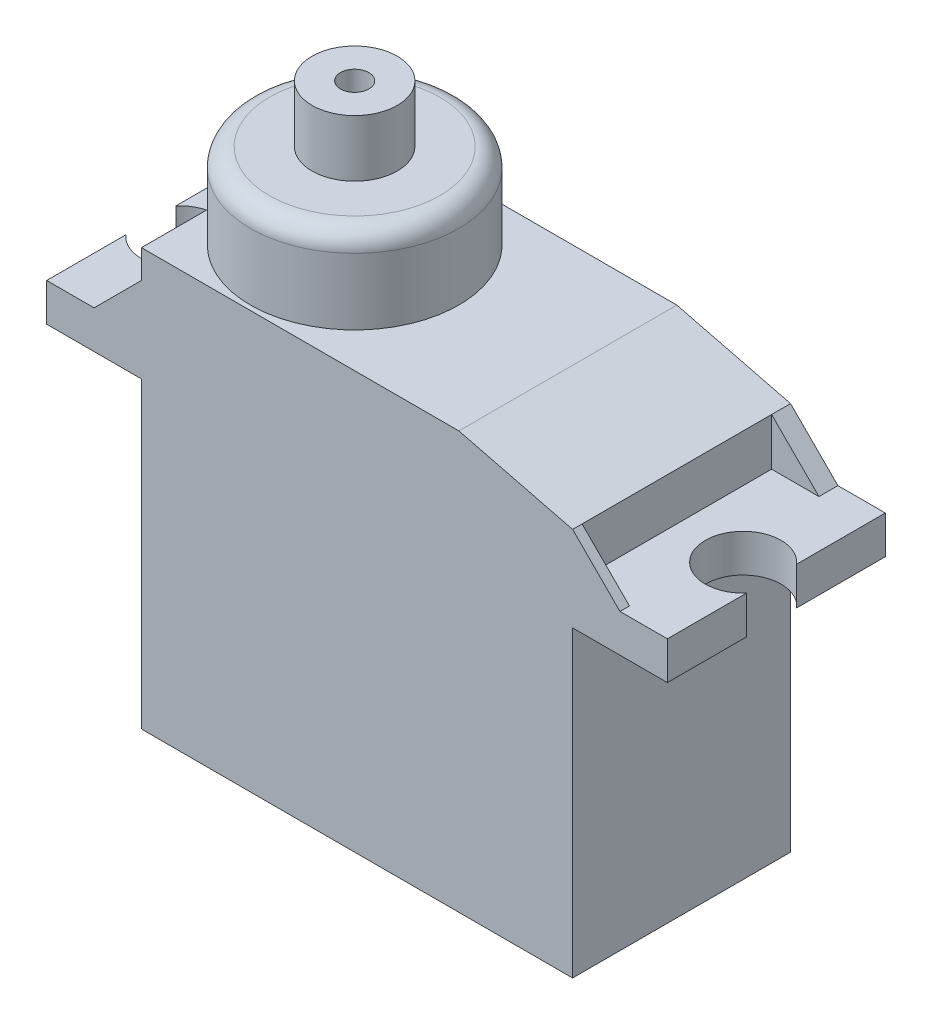
SolidWorks part; units mm, degrees
material "ABS"
ref_plane "Front Plane" through (0, 0, 0) normal (0, 0, 1) x (1, 0, 0)
ref_plane "Top Plane" through (0, 0, 0) normal (0, 1, 0) x (1, 0, 0)
ref_plane "Right Plane" through (0, 0, 0) normal (1, 0, 0) x (0, 0, -1)
sketch "Sketch1" plane through (0, 0, 0) normal (0, 1, 0) x (1, 0, 0)
  line L1 (0, 0) -> (22.75, 0)
  line L2 (0, 0) -> (0, 11.5)
  line L3 (0, 11.5) -> (22.75, 11.5)
  line L4 (22.75, 0) -> (22.75, 11.5)
  dimension "D1" = 11.5
  dimension "D2" = 22.75
extrude "Boss-Extrude1" add sketch "Sketch1" along normal blind 16
sketch "Sketch2" plane through (0, 0, 0) normal (0, 0, 1) x (1, 0, 0)
  line L0 (22.75, 16) -> (27.75, 16)
  line L1 (27.75, 16) -> (27.75, 18)
  line L2 (27.75, 18) -> (25.25, 18)
  line L3 (25.25, 18) -> (22.75, 20.5)
  line L4 (22.75, 20.5) -> (16.75, 22)
  line L5 (16.75, 22) -> (0, 22)
  line L6 (0, 22) -> (0, 20.5)
  line L7 (0, 20.5) -> (-2.5, 18)
  line L8 (-2.5, 18) -> (-5, 18)
  line L9 (-5, 18) -> (-5, 16)
  line L10 (-5, 16) -> (0, 16)
  line L11 (0, 16) -> (22.75, 16)
  line L12 (22.75, 16) -> (22.75, 0) construction
  dimension "D1" = 5
  dimension "D2" = 5
  dimension "D3" = 2.5
  dimension "D4" = 2.5
  dimension "D5" = 6
  dimension "D6" = 1.5
  dimension "D7" = 1.5
  dimension "D8" = 6
  dimension "D9" = 2
  dimension "D10" = 2
  dimension "D11" = 2.5
extrude "Boss-Extrude2" add sketch "Sketch2" against normal blind 11.5
sketch "Sketch3" plane through (0, 22, 0) normal (0, 1, 0) x (1, 0, 0)
  line L1 (16.75, 11.5) -> (0, 11.5) construction
  line L2 (0, 11.5) -> (0, 0) construction
  circle A0 centre (5.5, 5.75) radius 5.5
  dimension "D1" = 11
  dimension "D2" = 5.75
  dimension "D3" = 5.5
extrude "Boss-Extrude3" add sketch "Sketch3" along normal blind 4.5
fillet "Fillet1" radius 1 1 edges at (0, 26.5, -5.75)
sketch "Sketch5" plane through (0, 26.5, 0) normal (0, 1, 0) x (1, 0, 0)
  circle A0 centre (5.5, 5.75) radius 2.25
  dimension "D1" = 4.5
extrude "Boss-Extrude5" add sketch "Sketch5" along normal blind 3
sketch "Sketch6" plane through (0, 29.5, 0) normal (0, 1, 0) x (1, 0, 0)
  circle A0 centre (5.5, 5.75) radius 0.75
  circle A1 centre (5.5, 5.75) radius 2.25 construction
  dimension "D1" = 1.5
extrude "Cut-Extrude1" cut sketch "Sketch6" against normal blind 5
sketch "Sketch8" plane through (0, 0, 0) normal (0, 0, 1) x (1, 0, 0)
  line L0 (-2.5, 18) -> (0, 18)
  line L1 (0, 18) -> (0, 20.5)
  line L2 (0, 20.5) -> (-2.5, 18)
  line L3 (22.75, 20.5) -> (22.75, 18)
  line L4 (22.75, 18) -> (25.25, 18)
  line L5 (25.25, 18) -> (22.75, 20.5)
extrude "Cut-Extrude2" cut sketch "Sketch8" against normal blind 10 from offset 0.5 offset against normal yes
sketch "Sketch7" plane through (0, 18, 0) normal (0, 1, 0) x (1, 0, 0)
  line L0 (27.75, 0) -> (25.25, 0) construction
  line L1 (-2.5, 0) -> (-5, 0) construction
  line L2 (-5, 11.5) -> (-5, 0) construction
  line L3 (27.75, 11.5) -> (27.75, 0) construction
  circle A0 centre (26.25, 5.5) radius 2
  circle A1 centre (-3.5, 5.5) radius 2
  dimension "D1" = 4
  dimension "D3" = 5.5
  dimension "D2" = 5.5
  dimension "D4" = 1.5
  dimension "D5" = 1.5
extrude "Cut-Extrude3" cut sketch "Sketch7" against normal through all
